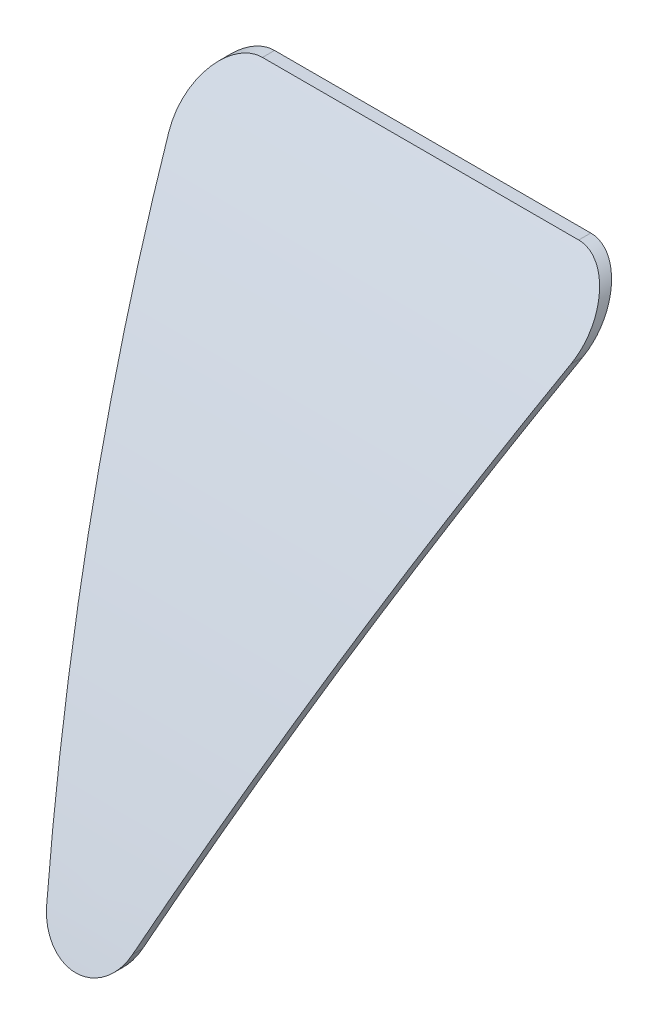
SolidWorks part; units mm, degrees
ref_plane "Front Plane" through (0, 0, 0) normal (0, 0, 1) x (1, 0, 0)
ref_plane "Top Plane" through (0, 0, 0) normal (0, 1, 0) x (1, 0, 0)
ref_plane "Right Plane" through (0, 0, 0) normal (1, 0, 0) x (0, 0, -1)
sketch "Sketch1" plane through (0, 0, 0) normal (1, 0, 0) x (0, 0, -1)
  line L0 (-975.275, 46.1239) -> (-918.9532, -10.198)
  line L1 (-1082.6326, -173.8774) -> (-1010.7918, -191.6358)
  spline S0 degree 3 poles (-762.6298, -2835.3055) (616.2347, 3520.0307) (-3587.7016, -3041.3271) (1612.0644, 799.4278) knots -0.938024 -0.938024 -0.938024 -0.938024 2.385725 2.385725 2.385725 2.385725 only from (-900, 44.5144) to (-1073.9479, -270) construction
  spline S1 degree 3 poles (-900, 44.5144) (-994.5703, -25.246) (-1068.5787, -155.0199) (-1073.9479, -270) knots 0.509799 0.509799 0.509799 0.509799 1 1 1 1
  spline S2 degree 1 poles (-901.1872, 46.1239) (-1075.9457, -269.9067) knots 0 0 1 1 construction
  spline S3 degree 3 poles (-901.1872, 46.1239) (-904.1742, 43.9205) (-910.0573, 39.4331) (-921.6993, 29.9692) (-935.882, 17.3414) (-952.2773, 0.9948) (-973.2005, -22.2363) (-997.4306, -53.6981) (-1022.8701, -94.4553) (-1044.1138, -137.3451) (-1057.8516, -174.14) (-1066.1796, -203.7734) (-1071.0232, -225.9917) (-1073.8307, -244.4016) (-1075.3044, -259.0335) (-1075.776, -266.2722) (-1075.9457, -269.9067) knots 0.509799 0.509799 0.509799 0.509799 0.525118 0.540437 0.571074 0.601712 0.632349 0.693625 0.7549 0.816175 0.87745 0.908087 0.938725 0.969362 0.984681 1 1 1 1
  dimension "D1" = 2
extrude "Boss-Extrude1" add sketch "Sketch1" along normal blind 60 and the other way blind 60 contours L0 S3 L1 S1
sketch "Sketch2" plane through (0, 0, 0) normal (0, 0, 1) x (1, 0, 0)
  line L0 (0, 42.0936) -> (0, -211.4308) construction
  line L1 (-87.8661, -13.7766) -> (89.7592, -13.7766) construction
  line L2 (-87.8661, -152.9252) -> (89.7592, -152.9252) construction
  line L3 (0.9465, -13.7766) -> (-34.7522, -13.7766)
  line L4 (-44.1874, -27.0898) -> (-9.4352, -126.056)
  line L5 (44.1874, -27.0898) -> (9.4352, -126.056)
  line L6 (-0.9465, -13.7766) -> (34.7522, -13.7766)
  line L8 (-87.8661, 34.1874) -> (124.0192, 34.1874)
  line L9 (-87.8661, 34.1874) -> (-87.8661, -211.4308)
  line L10 (-87.8661, -211.4308) -> (124.0192, -211.4308)
  line L11 (124.0192, 34.1874) -> (124.0192, -211.4308)
  arc A0 (-9.4352, -126.056) -> (9.4352, -126.056) centre (0, -122.7428) ccw
  arc A1 (44.1874, -27.0898) -> (34.7522, -13.7766) centre (34.7522, -23.7766) ccw
  arc A2 (-34.7522, -13.7766) -> (-44.1874, -27.0898) centre (-34.7522, -23.7766) ccw
  point P14 (0, -152.9252)
  point P17 (48.8623, -13.7766)
  point P20 (-48.8623, -13.7766)
  dimension "D1" = 10
extrude "Cut-Extrude1" cut sketch "Sketch2" along normal through all contours L11 L8 L9 L10 A2 L3 L6 A1 L5 A0 L4
